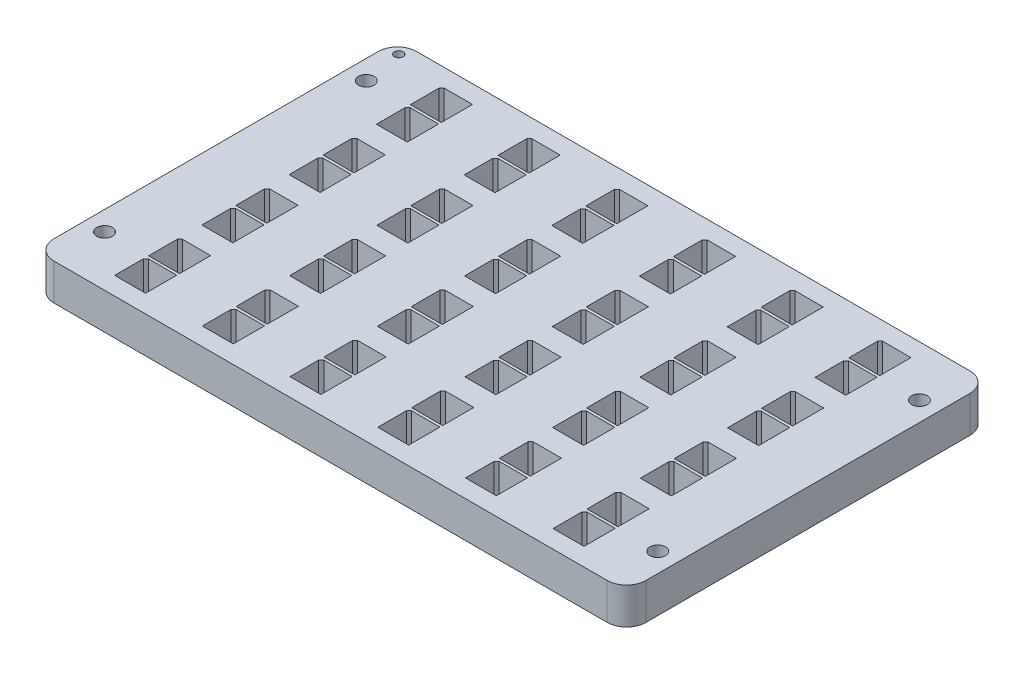
SolidWorks part; units mm, degrees
ref_plane "Front Plane" through (0, 0, 0) normal (0, 0, 1) x (1, 0, 0)
ref_plane "Top Plane" through (0, 0, 0) normal (0, 1, 0) x (1, 0, 0)
ref_plane "Right Plane" through (0, 0, 0) normal (1, 0, 0) x (0, 0, -1)
sketch "Sketch1" plane through (0, 0, 0) normal (0, 1, 0) x (1, 0, 0)
  line L0 (-57.055, 26.995) -> (57.055, 26.995) construction
  line L1 (61.055, 37.425) -> (-61.055, 37.425)
  line L2 (61.055, 37.425) -> (61.055, -37.425)
  line L3 (61.055, -37.425) -> (-61.055, -37.425)
  line L4 (-61.055, 37.425) -> (-61.055, -37.425)
  line L5 (61.055, 37.425) -> (-61.055, -37.425) construction
  line L6 (61.055, -37.425) -> (-61.055, 37.425) construction
  line L7 (57.055, 26.995) -> (57.055, -26.995) construction
  line L8 (57.055, -26.995) -> (-57.055, -26.995) construction
  line L9 (-57.055, -26.995) -> (-57.055, 26.995) construction
  line L10 (-57.055, 26.995) -> (-57.055, 37.425) construction
  line L11 (-57.055, 26.995) -> (-61.055, 26.995) construction
  line L12 (57.055, -26.995) -> (57.055, -37.425) construction
  line L13 (57.055, -26.995) -> (61.055, -26.995) construction
  circle A0 centre (-57.055, 26.995) radius 1.6
  circle A1 centre (57.055, 26.995) radius 1.6
  circle A2 centre (-57.055, -26.995) radius 1.6
  circle A3 centre (57.055, -26.995) radius 1.6
  point P0 (0, 0)
  dimension "D5" = 3.2
  dimension "D1" = 74.85
  dimension "D2" = 122.11
  dimension "D3" = 114.11
  dimension "D4" = 53.99
extrude "Boss-Extrude1" add sketch "Sketch1" along normal blind 7.5
sketch "Sketch2" plane through (0, 7.5, 0) normal (0, 1, 0) x (1, 0, 0)
  line L0 (-41.8678, 33.7138) -> (-47.7198, 33.7138)
  line L1 (-47.7198, 33.7138) -> (-48.2422, 33.1963)
  line L2 (-48.2422, 33.1963) -> (-48.2423, 27.2761)
  line L3 (-48.2423, 27.2761) -> (-41.8678, 27.2761)
  line L4 (-41.8678, 33.7138) -> (-41.8678, 27.2761)
  line L5 (-48.2423, 27.2761) -> (-41.8678, 33.7138) construction
  line L6 (-23.7778, 33.7138) -> (-23.7778, 27.2761)
  line L7 (-23.7778, 33.7138) -> (-29.6298, 33.7138)
  line L8 (-30.1523, 33.1963) -> (-30.1523, 27.2761)
  line L9 (-29.6298, 33.7138) -> (-30.1523, 33.1963)
  line L10 (-30.1523, 27.2761) -> (-23.7778, 27.2761)
  line L11 (-30.1523, 27.2761) -> (-23.7778, 33.7138) construction
  line L12 (-5.6878, 33.7138) -> (-5.6878, 27.2761)
  line L13 (-5.6878, 33.7138) -> (-11.5398, 33.7138)
  line L14 (-12.0623, 33.1963) -> (-12.0623, 27.2761)
  line L15 (-11.5398, 33.7138) -> (-12.0623, 33.1963)
  line L16 (-12.0623, 27.2761) -> (-5.6878, 27.2761)
  line L17 (-12.0623, 27.2761) -> (-5.6878, 33.7138) construction
  line L18 (12.4022, 33.7138) -> (12.4022, 27.2761)
  line L19 (12.4022, 33.7138) -> (6.5502, 33.7138)
  line L20 (6.0277, 33.1963) -> (6.0277, 27.2761)
  line L21 (6.5502, 33.7138) -> (6.0277, 33.1963)
  line L22 (6.0277, 27.2761) -> (12.4022, 27.2761)
  line L23 (6.0277, 27.2761) -> (12.4022, 33.7138) construction
  line L24 (30.4922, 33.7138) -> (30.4922, 27.2761)
  line L25 (30.4922, 33.7138) -> (24.6402, 33.7138)
  line L26 (24.1177, 33.1963) -> (24.1177, 27.2761)
  line L27 (24.6402, 33.7138) -> (24.1177, 33.1963)
  line L28 (24.1177, 27.2761) -> (30.4922, 27.2761)
  line L29 (24.1177, 27.2761) -> (30.4922, 33.7138) construction
  line L30 (48.5822, 33.7138) -> (48.5822, 27.2761)
  line L31 (48.5822, 33.7138) -> (42.7302, 33.7138)
  line L32 (42.2077, 33.1963) -> (42.2077, 27.2761)
  line L33 (42.7302, 33.7138) -> (42.2077, 33.1963)
  line L34 (42.2077, 27.2761) -> (48.5822, 27.2761)
  line L35 (42.2077, 27.2761) -> (48.5822, 33.7138) construction
  line L36 (-23.7777, 15.7139) -> (-23.7777, 9.2762)
  line L37 (-23.7777, 15.7139) -> (-29.6297, 15.7139)
  line L38 (-30.1522, 15.1964) -> (-30.1522, 9.2762)
  line L39 (-29.6297, 15.7139) -> (-30.1522, 15.1964)
  line L40 (-30.1522, 9.2762) -> (-23.7777, 9.2762)
  line L41 (-30.1522, 9.2762) -> (-23.7777, 15.7139) construction
  line L42 (-5.6877, 15.7139) -> (-5.6877, 9.2762)
  line L43 (-5.6877, 15.7139) -> (-11.5397, 15.7139)
  line L44 (-12.0622, 15.1964) -> (-12.0622, 9.2762)
  line L45 (-11.5397, 15.7139) -> (-12.0622, 15.1964)
  line L46 (-12.0622, 9.2762) -> (-5.6877, 9.2762)
  line L47 (-12.0622, 9.2762) -> (-5.6877, 15.7139) construction
  line L48 (12.4023, 15.7139) -> (12.4023, 9.2762)
  line L49 (12.4023, 15.7139) -> (6.5503, 15.7139)
  line L50 (6.0278, 15.1964) -> (6.0278, 9.2762)
  line L51 (6.5503, 15.7139) -> (6.0278, 15.1964)
  line L52 (6.0278, 9.2762) -> (12.4023, 9.2762)
  line L53 (6.0278, 9.2762) -> (12.4023, 15.7139) construction
  line L54 (30.4923, 15.7139) -> (30.4923, 9.2762)
  line L55 (30.4923, 15.7139) -> (24.6403, 15.7139)
  line L56 (24.1178, 15.1964) -> (24.1178, 9.2762)
  line L57 (24.6403, 15.7139) -> (24.1178, 15.1964)
  line L58 (24.1178, 9.2762) -> (30.4923, 9.2762)
  line L59 (24.1178, 9.2762) -> (30.4923, 15.7139) construction
  line L60 (48.5822, 15.7139) -> (48.5822, 9.2762)
  line L61 (48.5822, 15.7139) -> (42.7302, 15.7139)
  line L62 (42.2078, 15.1964) -> (42.2077, 9.2762)
  line L63 (42.7302, 15.7139) -> (42.2078, 15.1964)
  line L64 (42.2077, 9.2762) -> (48.5822, 9.2762)
  line L65 (42.2077, 9.2762) -> (48.5822, 15.7139) construction
  line L66 (-23.7777, -2.2861) -> (-23.7777, -8.7238)
  line L67 (-23.7777, -2.2861) -> (-29.6297, -2.2861)
  line L68 (-30.1522, -2.8036) -> (-30.1522, -8.7238)
  line L69 (-29.6297, -2.2861) -> (-30.1522, -2.8036)
  line L70 (-30.1522, -8.7238) -> (-23.7777, -8.7238)
  line L71 (-30.1522, -8.7238) -> (-23.7777, -2.2861) construction
  line L72 (-5.6877, -2.2861) -> (-5.6877, -8.7238)
  line L73 (-5.6877, -2.2861) -> (-11.5397, -2.2861)
  line L74 (-12.0622, -2.8036) -> (-12.0622, -8.7238)
  line L75 (-11.5397, -2.2861) -> (-12.0622, -2.8036)
  line L76 (-12.0622, -8.7238) -> (-5.6877, -8.7238)
  line L77 (-12.0622, -8.7238) -> (-5.6877, -2.2861) construction
  line L78 (12.4023, -2.2861) -> (12.4023, -8.7238)
  line L79 (12.4023, -2.2861) -> (6.5503, -2.2861)
  line L80 (6.0278, -2.8036) -> (6.0278, -8.7238)
  line L81 (6.5503, -2.2861) -> (6.0278, -2.8036)
  line L82 (6.0278, -8.7238) -> (12.4023, -8.7238)
  line L83 (6.0278, -8.7238) -> (12.4023, -2.2861) construction
  line L84 (30.4923, -2.2861) -> (30.4923, -8.7238)
  line L85 (30.4923, -2.2861) -> (24.6403, -2.2861)
  line L86 (24.1178, -2.8036) -> (24.1178, -8.7238)
  line L87 (24.6403, -2.2861) -> (24.1178, -2.8036)
  line L88 (24.1178, -8.7238) -> (30.4923, -8.7238)
  line L89 (24.1178, -8.7238) -> (30.4923, -2.2861) construction
  line L90 (48.5823, -2.2861) -> (48.5823, -8.7238)
  line L91 (48.5823, -2.2861) -> (42.7303, -2.2861)
  line L92 (42.2078, -2.8036) -> (42.2078, -8.7238)
  line L93 (42.7303, -2.2861) -> (42.2078, -2.8036)
  line L94 (42.2078, -8.7238) -> (48.5823, -8.7238)
  line L95 (42.2078, -8.7238) -> (48.5823, -2.2861) construction
  line L96 (-23.7777, -20.2861) -> (-23.7777, -26.7238)
  line L97 (-23.7777, -20.2861) -> (-29.6297, -20.2861)
  line L98 (-30.1522, -20.8036) -> (-30.1522, -26.7238)
  line L99 (-29.6297, -20.2861) -> (-30.1522, -20.8036)
  line L100 (-30.1522, -26.7238) -> (-23.7777, -26.7238)
  line L101 (-30.1522, -26.7238) -> (-23.7777, -20.2861) construction
  line L102 (-5.6877, -20.2861) -> (-5.6877, -26.7238)
  line L103 (-5.6877, -20.2861) -> (-11.5397, -20.2861)
  line L104 (-12.0622, -20.8036) -> (-12.0622, -26.7238)
  line L105 (-11.5397, -20.2861) -> (-12.0622, -20.8036)
  line L106 (-12.0622, -26.7238) -> (-5.6877, -26.7238)
  line L107 (-12.0622, -26.7238) -> (-5.6877, -20.2861) construction
  line L108 (12.4023, -20.2861) -> (12.4023, -26.7238)
  line L109 (12.4023, -20.2861) -> (6.5503, -20.2861)
  line L110 (6.0278, -20.8036) -> (6.0278, -26.7238)
  line L111 (6.5503, -20.2861) -> (6.0278, -20.8036)
  line L112 (6.0278, -26.7238) -> (12.4023, -26.7238)
  line L113 (6.0278, -26.7238) -> (12.4023, -20.2861) construction
  line L114 (30.4923, -20.2861) -> (30.4923, -26.7238)
  line L115 (30.4923, -20.2861) -> (24.6403, -20.2861)
  line L116 (24.1178, -20.8036) -> (24.1178, -26.7238)
  line L117 (24.6403, -20.2861) -> (24.1178, -20.8036)
  line L118 (24.1178, -26.7238) -> (30.4923, -26.7238)
  line L119 (24.1178, -26.7238) -> (30.4923, -20.2861) construction
  line L120 (48.5823, -20.2861) -> (48.5823, -26.7238)
  line L121 (48.5823, -20.2861) -> (42.7303, -20.2861)
  line L122 (42.2078, -20.8036) -> (42.2078, -26.7238)
  line L123 (42.7303, -20.2861) -> (42.2078, -20.8036)
  line L124 (42.2078, -26.7238) -> (48.5823, -26.7238)
  line L125 (42.2078, -26.7238) -> (48.5823, -20.2861) construction
  line L126 (-41.8677, 15.7139) -> (-41.8677, 9.2762)
  line L127 (-41.8677, 15.7139) -> (-47.7197, 15.7139)
  line L128 (-48.2422, 15.1964) -> (-48.2422, 9.2762)
  line L129 (-47.7197, 15.7139) -> (-48.2422, 15.1964)
  line L130 (-48.2422, 9.2762) -> (-41.8677, 9.2762)
  line L131 (-48.2422, 9.2762) -> (-41.8677, 15.7139) construction
  line L132 (-41.8677, -2.2861) -> (-41.8677, -8.7238)
  line L133 (-41.8677, -2.2861) -> (-47.7197, -2.2861)
  line L134 (-48.2422, -2.8036) -> (-48.2422, -8.7238)
  line L135 (-47.7197, -2.2861) -> (-48.2422, -2.8036)
  line L136 (-48.2422, -8.7238) -> (-41.8677, -8.7238)
  line L137 (-48.2422, -8.7238) -> (-41.8677, -2.2861) construction
  line L138 (-41.8677, -20.2861) -> (-41.8677, -26.7238)
  line L139 (-41.8677, -20.2861) -> (-47.7197, -20.2861)
  line L140 (-48.2422, -20.8036) -> (-48.2422, -26.7238)
  line L141 (-47.7197, -20.2861) -> (-48.2422, -20.8036)
  line L142 (-48.2422, -26.7238) -> (-41.8677, -26.7238)
  line L143 (-48.2422, -26.7238) -> (-41.8677, -20.2861) construction
  line L144 (-41.8678, 26.7138) -> (-47.7198, 26.7138)
  line L145 (-47.7198, 26.7138) -> (-48.2423, 26.1963)
  line L146 (-48.2423, 26.1963) -> (-48.2423, 20.2761)
  line L147 (-48.2423, 20.2761) -> (-41.8678, 20.2761)
  line L148 (-41.8678, 26.7138) -> (-41.8678, 20.2761)
  line L149 (-48.2423, 20.2761) -> (-41.8678, 26.7138) construction
  line L150 (-30.1523, 26.1963) -> (-30.1523, 20.2761)
  line L151 (-23.7778, 26.7138) -> (-23.7778, 20.2761)
  line L152 (-30.1523, 20.2761) -> (-23.7778, 20.2761)
  line L153 (-23.7778, 26.7138) -> (-29.6298, 26.7138)
  line L154 (-29.6298, 26.7138) -> (-30.1523, 26.1963)
  line L155 (-30.1523, 20.2761) -> (-23.7778, 26.7138) construction
  line L156 (-12.0623, 26.1963) -> (-12.0623, 20.2761)
  line L157 (-5.6878, 26.7138) -> (-5.6878, 20.2761)
  line L158 (-12.0623, 20.2761) -> (-5.6878, 20.2761)
  line L159 (-5.6878, 26.7138) -> (-11.5398, 26.7138)
  line L160 (-11.5398, 26.7138) -> (-12.0623, 26.1963)
  line L161 (-12.0623, 20.2761) -> (-5.6878, 26.7138) construction
  line L162 (6.0277, 26.1963) -> (6.0277, 20.2761)
  line L163 (12.4022, 26.7138) -> (12.4022, 20.2761)
  line L164 (6.0277, 20.2761) -> (12.4022, 20.2761)
  line L165 (12.4022, 26.7138) -> (6.5502, 26.7138)
  line L166 (6.5502, 26.7138) -> (6.0277, 26.1963)
  line L167 (6.0277, 20.2761) -> (12.4022, 26.7138) construction
  line L168 (24.1177, 26.1963) -> (24.1177, 20.2761)
  line L169 (30.4922, 26.7138) -> (30.4922, 20.2761)
  line L170 (24.1177, 20.2761) -> (30.4922, 20.2761)
  line L171 (30.4922, 26.7138) -> (24.6402, 26.7138)
  line L172 (24.6402, 26.7138) -> (24.1177, 26.1963)
  line L173 (24.1177, 20.2761) -> (30.4922, 26.7138) construction
  line L174 (42.2077, 26.1963) -> (42.2077, 20.2761)
  line L175 (48.5822, 26.7138) -> (48.5822, 20.2761)
  line L176 (42.2077, 20.2761) -> (48.5822, 20.2761)
  line L177 (48.5822, 26.7138) -> (42.7302, 26.7138)
  line L178 (42.7302, 26.7138) -> (42.2077, 26.1963)
  line L179 (42.2077, 20.2761) -> (48.5822, 26.7138) construction
  line L180 (-30.1522, 8.1964) -> (-30.1522, 2.2762)
  line L181 (-23.7777, 8.7139) -> (-23.7777, 2.2762)
  line L182 (-30.1522, 2.2762) -> (-23.7777, 2.2762)
  line L183 (-23.7777, 8.7139) -> (-29.6297, 8.7139)
  line L184 (-29.6297, 8.7139) -> (-30.1522, 8.1964)
  line L185 (-30.1522, 2.2762) -> (-23.7777, 8.7139) construction
  line L186 (-12.0622, 8.1964) -> (-12.0622, 2.2762)
  line L187 (-5.6877, 8.7139) -> (-5.6877, 2.2762)
  line L188 (-12.0622, 2.2762) -> (-5.6877, 2.2762)
  line L189 (-5.6877, 8.7139) -> (-11.5397, 8.7139)
  line L190 (-11.5397, 8.7139) -> (-12.0622, 8.1964)
  line L191 (-12.0622, 2.2762) -> (-5.6877, 8.7139) construction
  line L192 (6.0278, 8.1964) -> (6.0278, 2.2762)
  line L193 (12.4023, 8.7139) -> (12.4023, 2.2762)
  line L194 (6.0278, 2.2762) -> (12.4023, 2.2762)
  line L195 (12.4023, 8.7139) -> (6.5503, 8.7139)
  line L196 (6.5503, 8.7139) -> (6.0278, 8.1964)
  line L197 (6.0278, 2.2762) -> (12.4023, 8.7139) construction
  line L198 (24.1178, 8.1964) -> (24.1178, 2.2762)
  line L199 (30.4923, 8.7139) -> (30.4923, 2.2762)
  line L200 (24.1178, 2.2762) -> (30.4923, 2.2762)
  line L201 (30.4923, 8.7139) -> (24.6403, 8.7139)
  line L202 (24.6403, 8.7139) -> (24.1178, 8.1964)
  line L203 (24.1178, 2.2762) -> (30.4923, 8.7139) construction
  line L204 (42.2078, 8.1964) -> (42.2078, 2.2762)
  line L205 (48.5823, 8.7139) -> (48.5823, 2.2762)
  line L206 (42.2078, 2.2762) -> (48.5823, 2.2762)
  line L207 (48.5823, 8.7139) -> (42.7303, 8.7139)
  line L208 (42.7303, 8.7139) -> (42.2078, 8.1964)
  line L209 (42.2078, 2.2762) -> (48.5823, 8.7139) construction
  line L210 (-30.1522, -9.8036) -> (-30.1522, -15.7238)
  line L211 (-23.7777, -9.2861) -> (-23.7777, -15.7238)
  line L212 (-30.1522, -15.7238) -> (-23.7777, -15.7238)
  line L213 (-23.7777, -9.2861) -> (-29.6297, -9.2861)
  line L214 (-29.6297, -9.2861) -> (-30.1522, -9.8036)
  line L215 (-30.1522, -15.7238) -> (-23.7777, -9.2861) construction
  line L216 (-12.0622, -9.8036) -> (-12.0622, -15.7238)
  line L217 (-5.6877, -9.2861) -> (-5.6877, -15.7238)
  line L218 (-12.0622, -15.7238) -> (-5.6877, -15.7238)
  line L219 (-5.6877, -9.2861) -> (-11.5397, -9.2861)
  line L220 (-11.5397, -9.2861) -> (-12.0622, -9.8036)
  line L221 (-12.0622, -15.7238) -> (-5.6877, -9.2861) construction
  line L222 (6.0278, -9.8036) -> (6.0278, -15.7238)
  line L223 (12.4023, -9.2861) -> (12.4023, -15.7238)
  line L224 (6.0278, -15.7238) -> (12.4023, -15.7238)
  line L225 (12.4023, -9.2861) -> (6.5503, -9.2861)
  line L226 (6.5503, -9.2861) -> (6.0278, -9.8036)
  line L227 (6.0278, -15.7238) -> (12.4023, -9.2861) construction
  line L228 (24.1178, -9.8036) -> (24.1178, -15.7238)
  line L229 (30.4923, -9.2861) -> (30.4923, -15.7238)
  line L230 (24.1178, -15.7238) -> (30.4923, -15.7238)
  line L231 (30.4923, -9.2861) -> (24.6403, -9.2861)
  line L232 (24.6403, -9.2861) -> (24.1178, -9.8036)
  line L233 (24.1178, -15.7238) -> (30.4923, -9.2861) construction
  line L234 (42.2078, -9.8036) -> (42.2078, -15.7238)
  line L235 (48.5823, -9.2861) -> (48.5823, -15.7238)
  line L236 (42.2078, -15.7238) -> (48.5823, -15.7238)
  line L237 (48.5823, -9.2861) -> (42.7303, -9.2861)
  line L238 (42.7303, -9.2861) -> (42.2078, -9.8036)
  line L239 (42.2078, -15.7238) -> (48.5823, -9.2861) construction
  line L240 (-30.1522, -27.8036) -> (-30.1522, -33.7238)
  line L241 (-23.7777, -27.2861) -> (-23.7777, -33.7238)
  line L242 (-30.1522, -33.7238) -> (-23.7777, -33.7238)
  line L243 (-23.7777, -27.2861) -> (-29.6297, -27.2861)
  line L244 (-29.6297, -27.2861) -> (-30.1522, -27.8036)
  line L245 (-30.1522, -33.7238) -> (-23.7777, -27.2861) construction
  line L246 (-12.0622, -27.8036) -> (-12.0622, -33.7238)
  line L247 (-5.6877, -27.2861) -> (-5.6877, -33.7238)
  line L248 (-12.0622, -33.7238) -> (-5.6877, -33.7238)
  line L249 (-5.6877, -27.2861) -> (-11.5397, -27.2861)
  line L250 (-11.5397, -27.2861) -> (-12.0622, -27.8036)
  line L251 (-12.0622, -33.7238) -> (-5.6877, -27.2861) construction
  line L252 (6.0278, -27.8036) -> (6.0278, -33.7238)
  line L253 (12.4023, -27.2861) -> (12.4023, -33.7238)
  line L254 (6.0278, -33.7238) -> (12.4023, -33.7238)
  line L255 (12.4023, -27.2861) -> (6.5503, -27.2861)
  line L256 (6.5503, -27.2861) -> (6.0278, -27.8036)
  line L257 (6.0278, -33.7238) -> (12.4023, -27.2861) construction
  line L258 (24.1178, -27.8036) -> (24.1178, -33.7238)
  line L259 (30.4923, -27.2861) -> (30.4923, -33.7238)
  line L260 (24.1178, -33.7238) -> (30.4923, -33.7238)
  line L261 (30.4923, -27.2861) -> (24.6403, -27.2861)
  line L262 (24.6403, -27.2861) -> (24.1178, -27.8036)
  line L263 (24.1178, -33.7238) -> (30.4923, -27.2861) construction
  line L264 (42.2078, -27.8036) -> (42.2078, -33.7238)
  line L265 (48.5823, -27.2861) -> (48.5823, -33.7238)
  line L266 (42.2078, -33.7238) -> (48.5823, -33.7238)
  line L267 (48.5823, -27.2861) -> (42.7303, -27.2861)
  line L268 (42.7303, -27.2861) -> (42.2078, -27.8036)
  line L269 (42.2078, -33.7238) -> (48.5823, -27.2861) construction
  line L270 (-48.2422, 8.1964) -> (-48.2422, 2.2762)
  line L271 (-41.8677, 8.7139) -> (-41.8677, 2.2762)
  line L272 (-48.2422, 2.2762) -> (-41.8677, 2.2762)
  line L273 (-41.8677, 8.7139) -> (-47.7197, 8.7139)
  line L274 (-47.7197, 8.7139) -> (-48.2422, 8.1964)
  line L275 (-48.2422, 2.2762) -> (-41.8677, 8.7139) construction
  line L276 (-48.2422, -9.8036) -> (-48.2422, -15.7238)
  line L277 (-41.8677, -9.2861) -> (-41.8677, -15.7238)
  line L278 (-48.2422, -15.7238) -> (-41.8677, -15.7238)
  line L279 (-41.8677, -9.2861) -> (-47.7197, -9.2861)
  line L280 (-47.7197, -9.2861) -> (-48.2422, -9.8036)
  line L281 (-48.2422, -15.7238) -> (-41.8677, -9.2861) construction
  line L282 (-48.2422, -27.8036) -> (-48.2422, -33.7238)
  line L283 (-41.8677, -27.2861) -> (-41.8677, -33.7238)
  line L284 (-48.2422, -33.7238) -> (-41.8677, -33.7238)
  line L285 (-41.8677, -27.2861) -> (-47.7197, -27.2861)
  line L286 (-47.7197, -27.2861) -> (-48.2422, -27.8036)
  line L287 (-48.2422, -33.7238) -> (-41.8677, -27.2861) construction
  circle A0 centre (-57.055, 26.995) radius 1.6 construction
  circle A1 centre (-58.4431, 35.0714) radius 0.8992
  point P0 (-45.055, 30.495)
  point P2 (-45.055, 23.495)
  point P9 (-26.965, 30.495)
  point P17 (-8.875, 30.495)
  point P23 (9.215, 30.495)
  point P29 (27.305, 30.495)
  point P35 (45.395, 30.495)
  point P41 (-26.965, 12.495)
  point P47 (-8.875, 12.495)
  point P53 (9.215, 12.495)
  point P59 (27.305, 12.495)
  point P65 (45.395, 12.495)
  point P71 (-26.965, -5.505)
  point P77 (-8.875, -5.505)
  point P83 (9.215, -5.505)
  point P89 (27.305, -5.505)
  point P95 (45.395, -5.505)
  point P101 (-26.965, -23.505)
  point P107 (-8.875, -23.505)
  point P113 (9.215, -23.505)
  point P119 (27.305, -23.505)
  point P125 (45.395, -23.505)
  point P131 (-45.055, 12.495)
  point P137 (-45.055, -5.505)
  point P143 (-45.055, -23.505)
  point P155 (-26.965, 23.495)
  point P161 (-8.875, 23.495)
  point P167 (9.215, 23.495)
  point P173 (27.305, 23.495)
  point P179 (45.395, 23.495)
  point P185 (-26.965, 5.495)
  point P191 (-8.875, 5.495)
  point P197 (9.215, 5.495)
  point P203 (27.305, 5.495)
  point P209 (45.395, 5.495)
  point P215 (-26.965, -12.505)
  point P221 (-8.875, -12.505)
  point P227 (9.215, -12.505)
  point P233 (27.305, -12.505)
  point P239 (45.395, -12.505)
  point P245 (-26.965, -30.505)
  point P251 (-8.875, -30.505)
  point P257 (9.215, -30.505)
  point P263 (27.305, -30.505)
  point P269 (45.395, -30.505)
  point P275 (-45.055, 5.495)
  point P281 (-45.055, -12.505)
  point P287 (-45.055, -30.505)
  dimension "D1" = 6.3745
  dimension "D2" = 6.4377
  dimension "D3" = 5.852
  dimension "D4" = 5.9202
  dimension "D5" = 0.7354
  dimension "D6" = 12
  dimension "D7" = 3.5
  dimension "D8" = 6
  dimension "D9" = 4
  dimension "D10" = 5.852
  dimension "D11" = 5.9202
  dimension "D12" = 6.4377
  dimension "D13" = 6.3745
  dimension "D14" = 0.7354
  dimension "D15" = 12
  dimension "D16" = 3.5
extrude "Cut-Extrude1" cut sketch "Sketch2" against normal through all
fillet "Fillet1" radius 4 4 edges at (61.055, 3.75, 37.425) (-61.055, 3.75, 37.425) (61.055, 3.75, -37.425) (-61.055, 3.75, -37.425)
